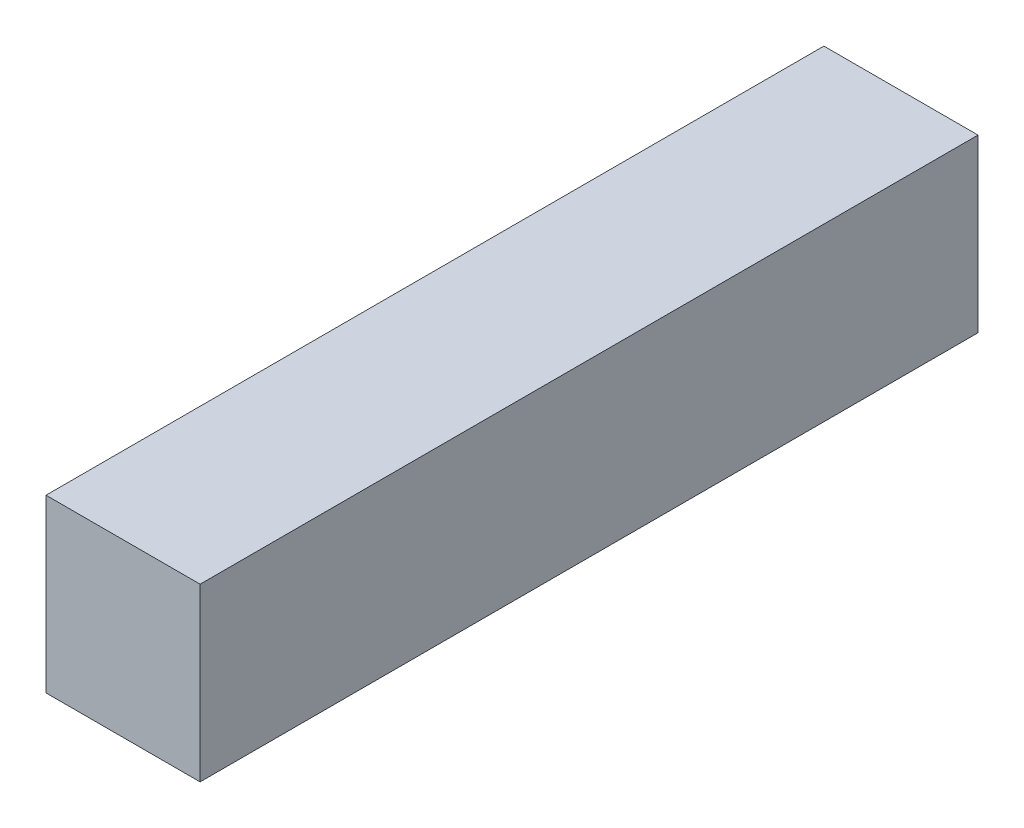
SolidWorks part; units mm, degrees
ref_plane "Plan de face" through (0, 0, 0) normal (0, 0, 1) x (1, 0, 0)
ref_plane "Plan de dessus" through (0, 0, 0) normal (0, 1, 0) x (1, 0, 0)
ref_plane "Plan de droite" through (0, 0, 0) normal (1, 0, 0) x (0, 0, -1)
sketch "Esquisse1" plane through (0, 0, 0) normal (0, 0, 1) x (1, 0, 0)
  line L1 (0, 0) -> (-63, 0)
  line L2 (0, 0) -> (0, 70)
  line L3 (0, 70) -> (-63, 70)
  line L4 (-63, 0) -> (-63, 70)
  dimension "D1" = 70
  dimension "D2" = 63
extrude "Boss.-Extru.1" add sketch "Esquisse1" along normal blind 318
